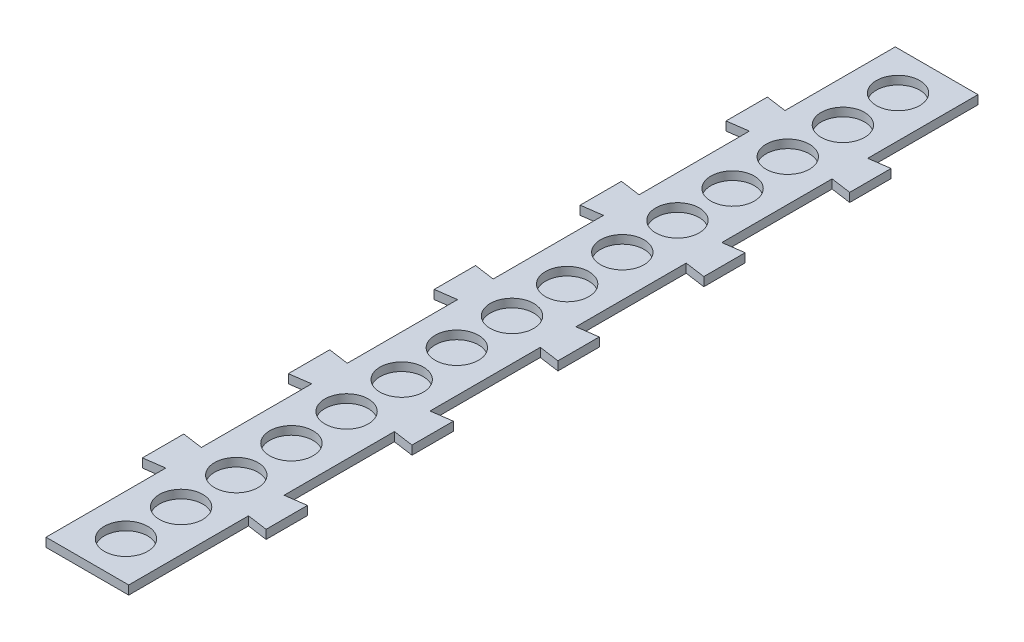
SolidWorks part; units mm, degrees
ref_plane "Front Plane" through (0, 0, 0) normal (0, 0, 1) x (1, 0, 0)
ref_plane "Top Plane" through (0, 0, 0) normal (0, 1, 0) x (1, 0, 0)
ref_plane "Right Plane" through (0, 0, 0) normal (1, 0, 0) x (0, 0, -1)
sketch "Sketch1" plane through (0, 0, 0) normal (0, 1, 0) x (1, 0, 0)
  line L1 (-19.05, -195.58) -> (19.05, -195.58)
  line L2 (-19.05, -195.58) -> (-19.05, 195.58)
  line L3 (-19.05, 195.58) -> (19.05, 195.58)
  line L4 (19.05, -195.58) -> (19.05, 195.58)
  line L5 (-19.05, -195.58) -> (19.05, 195.58) construction
  line L6 (-19.05, 195.58) -> (19.05, -195.58) construction
  point P0 (0, 0)
  dimension "D1" = 391.16
  dimension "D2" = 38.1
extrude "Boss-Extrude1" add sketch "Sketch1" along normal blind 4.064
sketch "Sketch2" plane through (0, 4.064, 0) normal (0, 1, 0) x (1, 0, 0)
  line L0 (-19.05, 195.58) -> (-19.05, -195.58) construction
  line L1 (19.05, 195.58) -> (-19.05, 195.58) construction
  line L3 (-19.05, -195.58) -> (19.05, -195.58) construction
  circle A0 centre (0, 177.8) radius 10
  circle A1 centre (0, 152.4) radius 10
  circle A2 centre (0, 127) radius 10
  circle A3 centre (0, 101.6) radius 10
  circle A4 centre (0, 76.2) radius 10
  circle A5 centre (0, 50.8) radius 10
  circle A6 centre (0, 25.4) radius 10
  circle A7 centre (0, 0) radius 10
  circle A8 centre (0, -25.4) radius 10
  circle A9 centre (0, -50.8) radius 10
  circle A10 centre (0, -76.2) radius 10
  circle A11 centre (0, -101.6) radius 10
  circle A12 centre (0, -127) radius 10
  circle A13 centre (0, -152.4) radius 10
  circle A14 centre (0, -177.8) radius 10
  dimension "D1" = 20
  dimension "D2" = 19.05
  dimension "D4" = 17.78
  dimension "D5" = 17.78
  dimension "D3" = 15
extrude "Cut-Extrude1" cut sketch "Sketch2" against normal blind 3.864
sketch "Sketch4" plane through (0, 0, 0) normal (0, 1, 0) x (1, 0, 0)
  line L0 (19.05, -56.8163) -> (28.4823, -55.4906)
  line L2 (19.05, -195.58) -> (19.05, 195.58) construction
  line L5 (19.05, 144.78) -> (19.05, 128.3812)
  line L6 (0, 195.58) -> (0, -195.58) construction
  line L7 (19.05, 195.58) -> (-19.05, 195.58) construction
  line L8 (-19.05, -195.58) -> (19.05, -195.58) construction
  line L9 (19.05, -56.8163) -> (19.05, -73.215)
  line L30 (-19.05, 144.78) -> (-19.05, 128.3812)
  line L31 (19.05, 144.78) -> (28.4823, 146.1056)
  line L32 (-19.05, 128.3812) -> (-28.4823, 127.0556)
  line L33 (19.05, 128.3812) -> (28.4823, 127.0556)
  line L34 (28.4823, 146.1056) -> (28.4823, 127.0556)
  line L35 (19.05, 144.78) -> (19.05, 128.3812)
  line L36 (19.05, 144.78) -> (19.05, 128.3812)
  line L37 (28.4823, 127.0556) -> (28.4823, 146.1056)
  line L38 (19.05, 144.78) -> (28.4823, 146.1056)
  line L39 (-19.05, 144.78) -> (-28.4823, 146.1056)
  line L40 (-28.4823, 127.0556) -> (-28.4823, 146.1056)
  line L41 (-28.4823, 146.1056) -> (-28.4823, 127.0556)
  line L42 (19.05, 77.5812) -> (28.4823, 78.9069)
  line L43 (19.05, 77.5812) -> (19.05, 61.1825)
  line L44 (19.05, 61.1825) -> (28.4823, 59.8569)
  line L45 (28.4823, 78.9069) -> (28.4823, 59.8569)
  line L46 (19.05, 10.3825) -> (28.4823, 11.7081)
  line L47 (19.05, 10.3825) -> (19.05, -6.0163)
  line L48 (19.05, -6.0163) -> (28.4823, -7.3419)
  line L49 (28.4823, 11.7081) -> (28.4823, -7.3419)
  line L50 (-19.05, 10.3825) -> (-19.05, -6.0163)
  line L51 (-19.05, -6.0163) -> (-28.4823, -7.3419)
  line L52 (-28.4823, 11.7081) -> (-28.4823, -7.3419)
  line L53 (-19.05, 10.3825) -> (-28.4823, 11.7081)
  line L54 (-19.05, 77.5812) -> (-19.05, 61.1825)
  line L55 (-19.05, 61.1825) -> (-28.4823, 59.8569)
  line L56 (-28.4823, 78.9069) -> (-28.4823, 59.8569)
  line L57 (-19.05, 77.5812) -> (-28.4823, 78.9069)
  line L58 (19.05, -73.215) -> (28.4823, -74.5406)
  line L59 (28.4823, -55.4906) -> (28.4823, -74.5406)
  line L60 (19.05, -124.015) -> (28.4823, -122.6894)
  line L61 (19.05, -124.015) -> (19.05, -140.4138)
  line L62 (19.05, -140.4138) -> (28.4823, -141.7394)
  line L63 (28.4823, -122.6894) -> (28.4823, -141.7394)
  line L72 (-19.05, -124.015) -> (-19.05, -140.4138)
  line L73 (-19.05, -140.4138) -> (-28.4823, -141.7394)
  line L74 (-28.4823, -122.6894) -> (-28.4823, -141.7394)
  line L75 (-19.05, -124.015) -> (-28.4823, -122.6894)
  line L76 (-19.05, -56.8163) -> (-19.05, -73.215)
  line L77 (-19.05, -73.215) -> (-28.4823, -74.5406)
  line L78 (-28.4823, -55.4906) -> (-28.4823, -74.5406)
  line L79 (-19.05, -56.8163) -> (-28.4823, -55.4906)
  line L80 (19.05, 144.78) -> (28.4823, 144.78) construction
  line L81 (19.05, 128.3812) -> (28.4823, 128.3812) construction
  dimension "D1" = 8
  dimension "D2" = 8
  dimension "D3" = 9.525
  dimension "D4" = 19.05
  dimension "D5" = 50.8
  dimension "D6" = 5
  dimension "D7" = 50.8
extrude "Boss-Extrude2" add sketch "Sketch4" along normal blind 4.064 contours L54 L57 L56 L55 | L50 L53 L52 L51 | L49 L46 L47 L48 | L40 L32 L30 L39 | L34 L31 L5 L33
